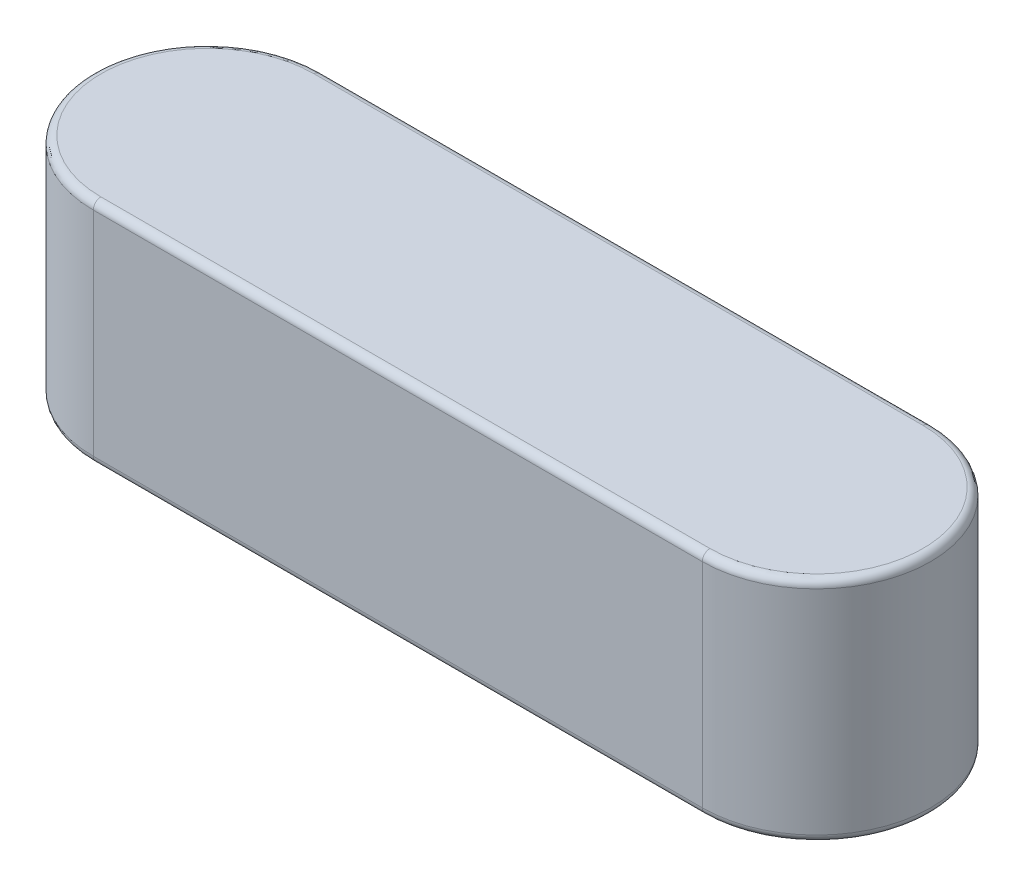
SolidWorks part; units mm, degrees
material "1060 Alloy"
ref_plane "Front Plane" through (0, 0, 0) normal (0, 0, 1) x (1, 0, 0)
ref_plane "Top Plane" through (0, 0, 0) normal (0, 1, 0) x (1, 0, 0)
ref_plane "Right Plane" through (0, 0, 0) normal (1, 0, 0) x (0, 0, -1)
sketch "Sketch1" plane through (0, 0, 0) normal (0, 1, 0) x (1, 0, 0)
  line L0 (0, 0) -> (16, 0) construction
  line L1 (0, 3) -> (16, 3)
  line L2 (0, -3) -> (16, -3)
  arc A0 (0, 3) -> (0, -3) centre (0, 0) ccw
  arc A1 (16, -3) -> (16, 3) centre (16, 0) ccw
  point P3 (8, 0)
  dimension "D1" = 3
  dimension "D2" = 16
extrude "Boss-Extrude1" add sketch "Sketch1" along normal blind 6
fillet "Fillet1" radius 0.2 8 edges at (-3, 6, 0) (8, 6, -3) (19, 6, 0) (-3, 0, 0) (8, 0, -3) (19, 0, 0) (8, 6, 3) (8, 0, 3)
